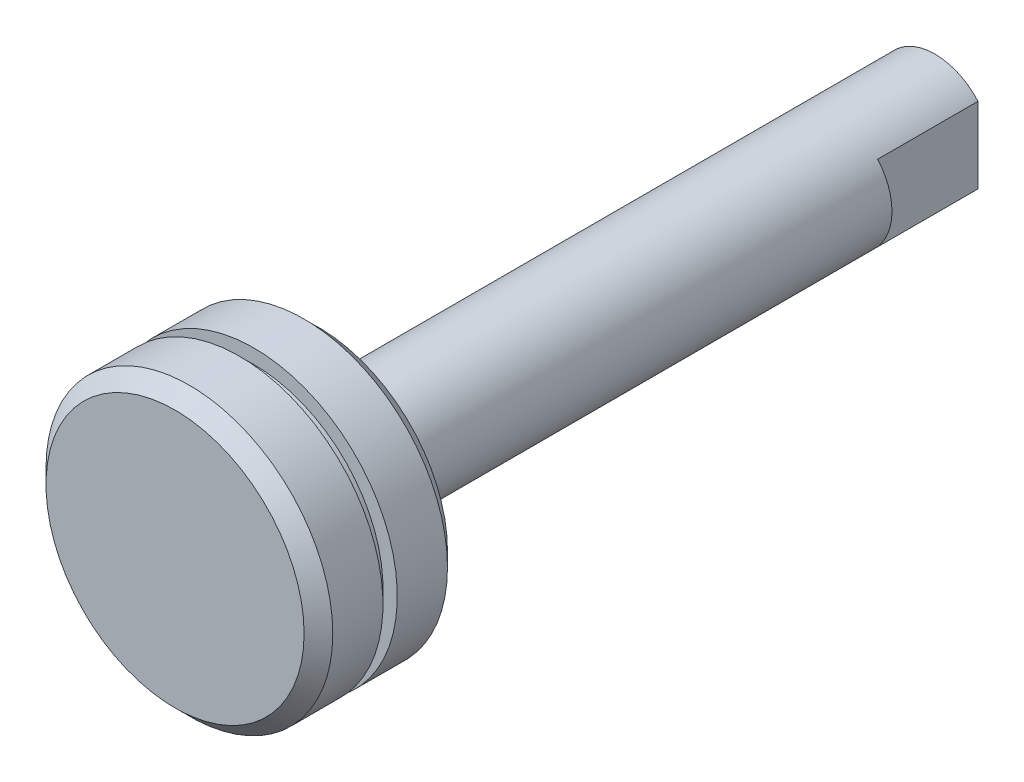
SolidWorks part; units mm, degrees
ref_plane "Plane1" through (0, 0, 0) normal (0, 0, 1) x (1, 0, 0)
ref_plane "Plane2" through (0, 0, 0) normal (0, 1, 0) x (1, 0, 0)
ref_plane "Plane3" through (0, 0, 0) normal (1, 0, 0) x (0, 0, -1)
sketch "Esquisse1" plane through (0, 0, 0) normal (0, 0, 1) x (1, 0, 0)
  circle A0 centre (0, 0) radius 4
  dimension "D1" = 8
extrude "Base-Extrusion" add sketch "Esquisse1" along normal blind 43
sketch "Esquisse2" plane through (0, 0, 43) normal (0, 0, 1) x (1, 0, 0)
  circle A0 centre (0, 0) radius 10
  dimension "D1" = 20
extrude "Boss.-Extru.1" add sketch "Esquisse2" along normal blind 10
sketch "Esquisse4" plane through (0, 0, 0) normal (0, 0, -1) x (-1, 0, 0)
  line L1 (3, 4.1026) -> (6.3142, 4.1026)
  line L2 (3, 4.1026) -> (3, -3.9095)
  line L3 (3, -3.9095) -> (6.3142, -3.9095)
  line L4 (6.3142, 4.1026) -> (6.3142, -3.9095)
  line L5 (-3, 4.1026) -> (-6.0568, 4.1026)
  line L6 (-3, 4.1026) -> (-3, -4.1669)
  line L7 (-3, -4.1669) -> (-6.0568, -4.1669)
  line L8 (-6.0568, 4.1026) -> (-6.0568, -4.1669)
  dimension "D1" = 3
  dimension "D2" = 3
extrude "Enlèv. mat.-Extru.1" cut sketch "Esquisse4" against normal blind 7
chamfer "Chanfrein2" distance 1 angle 45 2 edges at (10, 0, 53) (10, 0, 43)
sketch "Esquisse6" plane through (0, 0, 0) normal (1, 0, 0) x (0, 0, -1)
  line L0 (-53, 9) -> (-53, -9) construction
  line L1 (-48.5, 10) -> (-47.5, 10)
  line L2 (-48.5, 10) -> (-48.5, 9)
  line L3 (-48.5, 9) -> (-47.5, 9)
  line L4 (-47.5, 10) -> (-47.5, 9)
  line L5 (-44, 10) -> (-52, 10) construction
  line L6 (-53, 0) -> (-56.4888, 0) construction
  dimension "D1" = 1
  dimension "D2" = 1
  dimension "D3" = 4.5
revolve "Enlèvement de matière-Révolution2" cut sketch "Esquisse6" angle 360 about L6
hole_wizard "Trou taraudé M5x0.81" positions "Esquisse9" profile "Esquisse8" tap size "M5x0.8" standard "Ansi Métrique"
sketch "Esquisse9" plane through (0, 0, 0) normal (0, 0, -1) x (-1, 0, 0)
  point P0 (0, 0)
sketch "Esquisse8" plane through (0, 0, 0) normal (1, 0, 0) x (0, 1, 0)
  line L0 (0, 0) -> (0, 20.2618)
  line L1 (0, 20.2618) -> (2.1, 19)
  line L2 (2.1, 19) -> (2.1, 0)
  line L5 (2.1, 0) -> (0, 0)
  line L10 (0, 20.2618) -> (-2.1, 19) construction
  line L11 (0, -6.35) -> (0, 107.95) construction
  dimension "Diamètre du trou pour taraudage" = 4.2
  dimension "Profondeur du trou pour taraudage" = 19
  dimension "Angle de pointe" = 118
cosmetic thread "Filetage de perçage1" parameters "D1"=15, "D2"=5
sketch "Esquisse10" plane through (0, 0, 43) normal (0, 0, -1) x (-1, 0, 0)
  circle A0 centre (0, 0) radius 7.5
  circle A1 centre (0, 0) radius 6.5
  dimension "D1" = 15
  dimension "D2" = 13
extrude "Enlèv. mat.-Extru.2" cut sketch "Esquisse10" against normal blind 2
